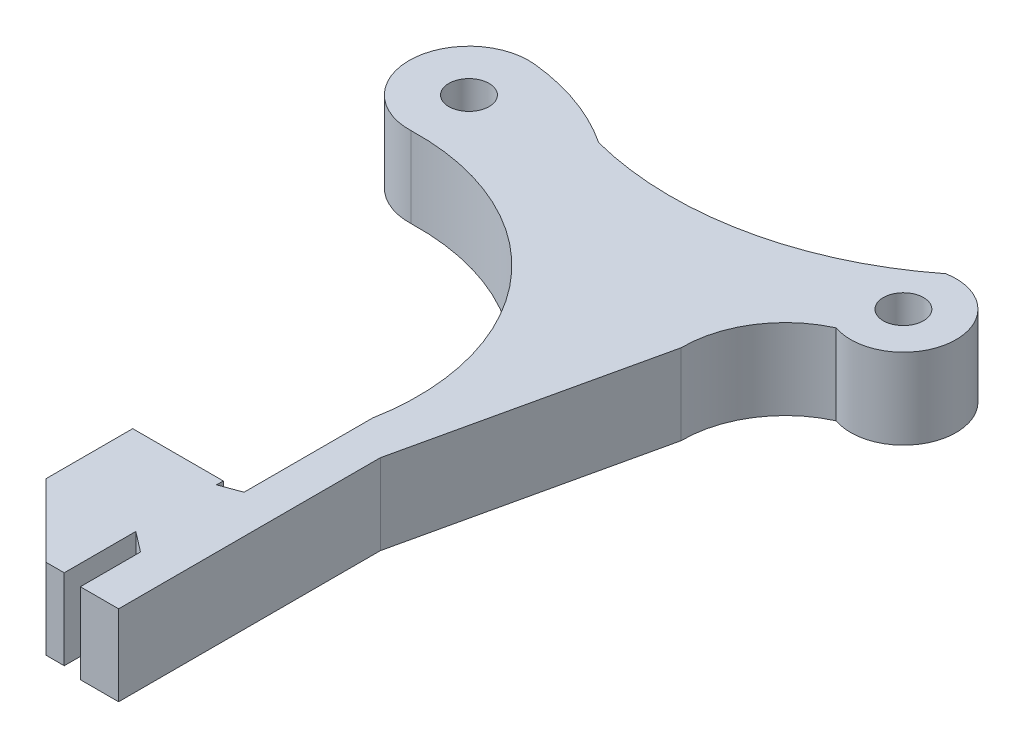
SolidWorks part; units mm, degrees
ref_plane "Front Plane" through (0, 0, 0) normal (0, 0, 1) x (1, 0, 0)
ref_plane "Top Plane" through (0, 0, 0) normal (0, 1, 0) x (1, 0, 0)
ref_plane "Right Plane" through (0, 0, 0) normal (1, 0, 0) x (0, 0, -1)
sketch "Sketch1" plane through (0, 0, 0) normal (0, 1, 0) x (1, 0, 0)
  line L0 (-90.9036, 63.2256) -> (22.3091, 63.2256) construction
  line L1 (-15, 0) -> (15, 0) construction
  line L2 (-26.25, 10.75) -> (-15, 10.75)
  line L3 (-15, 10.75) -> (-15, 0)
  line L4 (-15, 0) -> (-23.9848, -9)
  line L5 (-23.9848, -9) -> (-26.25, -9)
  line L6 (-26.25, -9) -> (-26.25, -0.1143)
  line L7 (-26.25, 9.912) -> (-29.4384, 11.0733)
  line L8 (-29.4384, 11.0733) -> (-29.4384, -2.5551)
  line L9 (-29.4384, -2.5551) -> (-26.25, -0.1143)
  line L10 (-26.25, 10.75) -> (-26.25, 9.912)
  line L11 (0, 0) -> (0, 30.0291) construction
  line L12 (26.25, 10.75) -> (26.25, 9.912)
  line L13 (29.4384, -2.5551) -> (26.25, -0.1143)
  line L14 (29.4384, 11.0733) -> (29.4384, -2.5551)
  line L15 (26.25, 9.912) -> (29.4384, 11.0733)
  line L16 (26.25, -9) -> (26.25, -0.1143)
  line L17 (23.9848, -9) -> (26.25, -9)
  line L18 (15, 0) -> (23.9848, -9)
  line L19 (15, 10.75) -> (15, 0)
  line L20 (26.25, 10.75) -> (15, 10.75)
  point P6 (0, 0)
  dimension "D1" = 30
  dimension "D2" = 10.75
  dimension "D3" = 11.25
  dimension "D4" = 19.75
  dimension "D5" = 12.7171
extrude "Boss-Extrude2" add sketch "Sketch1" along normal blind 10
sketch "Sketch4" plane through (0, 0, 0) normal (0, 1, 0) x (1, 0, 0)
  line L0 (28.75, -9.5) -> (33.5, -9.5)
  line L1 (33.5, -9.5) -> (33.5, 22.9965)
  line L2 (28.75, -9.5) -> (28.75, 26.7887)
  line L3 (0, 0) -> (0, 30.0291) construction
  line L4 (33.5, 22.9965) -> (40.3452, 53.4782)
  arc A0 (40.3452, 53.4782) -> (47.8361, 65.2616) centre (53.171, 53.5974) cw
  arc A1 (47.8361, 65.2616) -> (48.8157, 77.8865) centre (50, 71.4442) ccw
  circle A3 centre (0, 67.5) radius 2.5
  arc A4 (0.7653, 74.889) -> (0.2261, 60.0749) centre (0, 67.5) ccw
  arc A5 (0.2261, 60.0749) -> (28.75, 26.7887) centre (1.0829, 31.9445) cw
  arc A6 (0.7653, 74.889) -> (13.1801, 70.4305) centre (-2.0748, 47.4666) cw
  arc A7 (13.1801, 70.4305) -> (48.8157, 77.8865) centre (23.4651, 110.1615) ccw
  circle A8 centre (50, 71.4442) radius 2.5
  point P23 (64.8954, 75.4609)
  dimension "D4" = 5
  dimension "D1" = 28.75
  dimension "D2" = 4.75
  dimension "D3" = 9.5
  dimension "D5" = 67.5
  dimension "D6" = 50
  dimension "D7" = 71.4442
extrude "Boss-Extrude3" add sketch "Sketch4" along normal blind 10
sketch "Sketch8" plane through (0, 0, 0) normal (0, 1, 0) x (1, 0, 0)
  circle A0 centre (-20.9054, 4.1926) radius 22.8393
extrude "Cut-Extrude1" cut sketch "Sketch8" along normal blind 10
